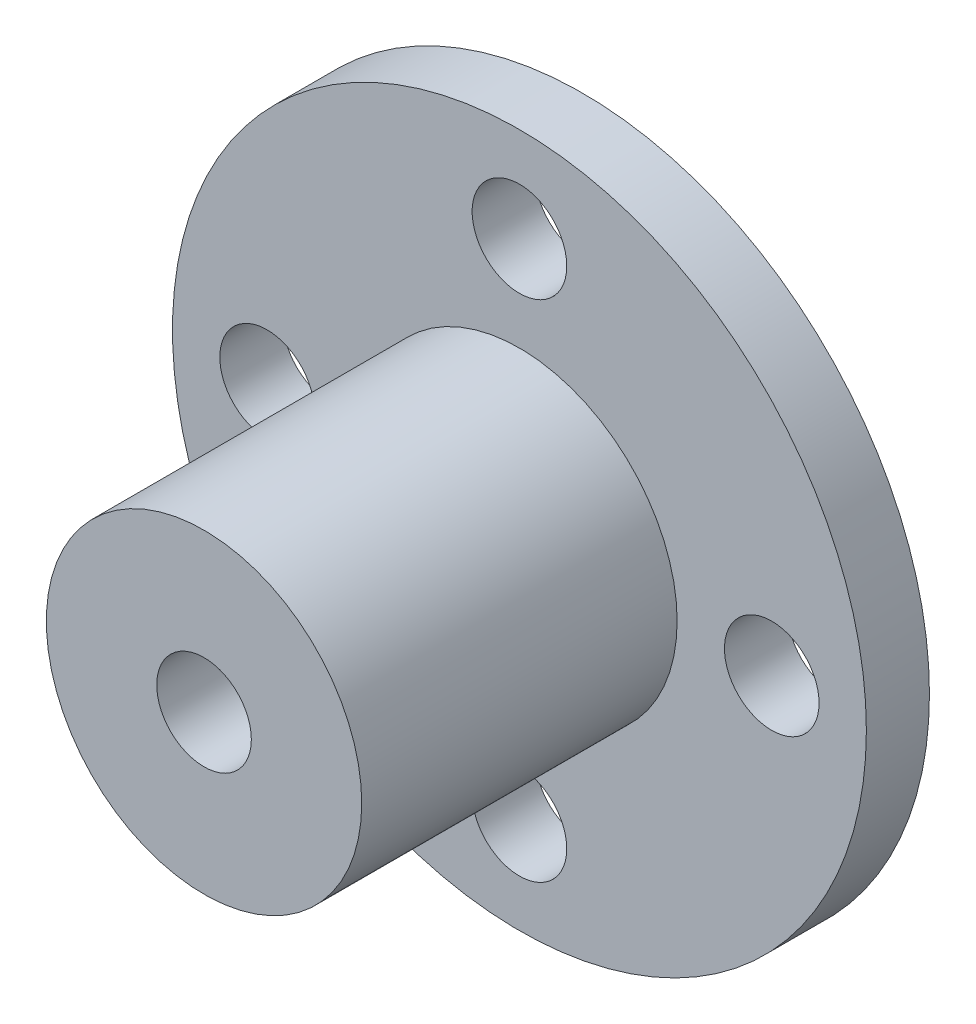
SolidWorks part; units mm, degrees
ref_plane "前视基准面" through (0, 0, 0) normal (0, 0, 1) x (1, 0, 0)
ref_plane "上视基准面" through (0, 0, 0) normal (0, 1, 0) x (1, 0, 0)
ref_plane "右视基准面" through (0, 0, 0) normal (1, 0, 0) x (0, 0, -1)
sketch "草图1" plane through (0, 0, 0) normal (0, 0, 1) x (1, 0, 0)
  line L0 (0, 0) -> (0, 15.0013) construction
  line L1 (0, 0) -> (18.2065, 0) construction
  circle A0 centre (0, 0) radius 11
  circle A1 centre (0, 0) radius 8
  circle A2 centre (0, 8) radius 1.5
  circle A3 centre (8, 0) radius 1.5
  circle A4 centre (0, -8) radius 1.5
  circle A5 centre (-8, 0) radius 1.5
  dimension "D1" = 22
  dimension "D2" = 16
  dimension "D3" = 3
extrude "凸台-拉伸1" add sketch "草图1" along normal blind 2 contours A0 A5 A1 A2 A3 A4 | A5 A1 A4 A3 A2
sketch "草图4" plane through (0, 0, 2) normal (0, 0, 1) x (1, 0, 0)
  circle A0 centre (0, 0) radius 5
  dimension "D1" = 10
extrude "凸台-拉伸3" add sketch "草图4" along normal blind 10
sketch "草图5" plane through (0, 0, 12) normal (0, 0, 1) x (1, 0, 0)
  circle A0 centre (0, 0) radius 1.5
  dimension "D1" = 3
extrude "切除-拉伸2" cut sketch "草图5" against normal through all
